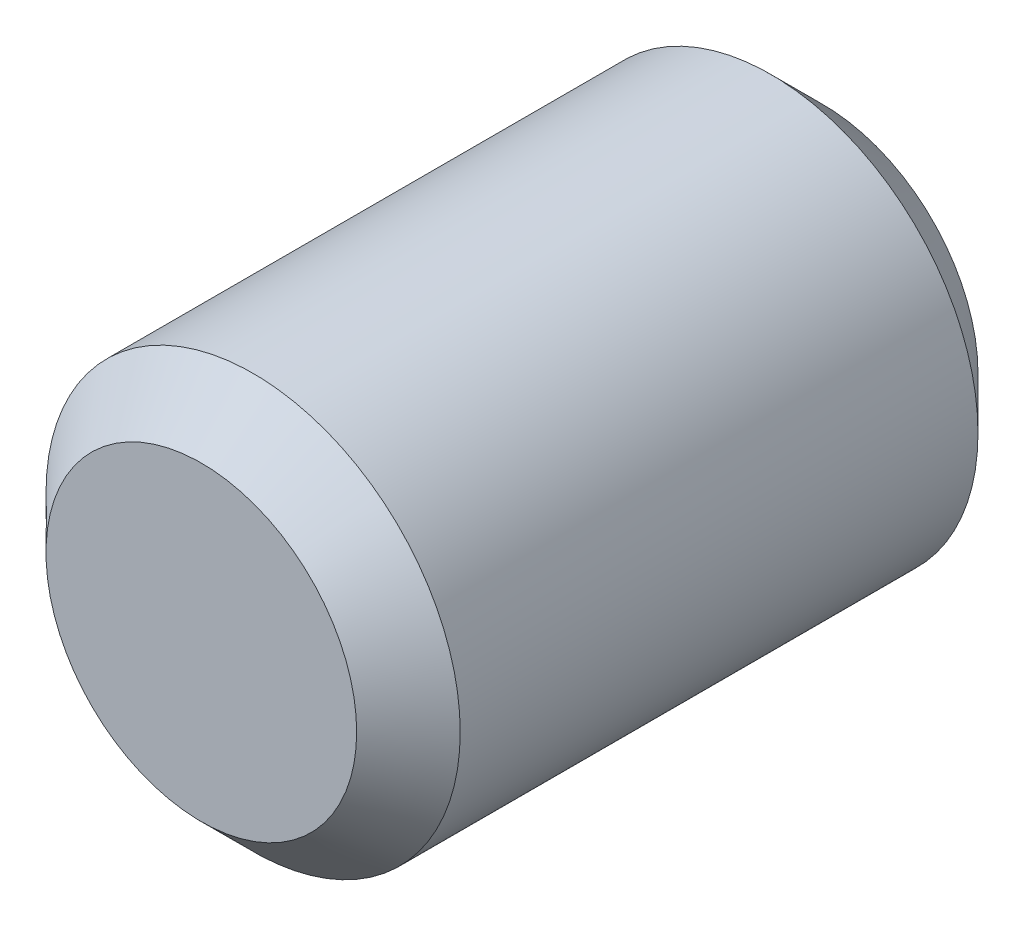
SolidWorks part; units mm, degrees
ref_plane "Front" through (0, 0, 0) normal (0, 0, 1) x (1, 0, 0)
ref_plane "Top" through (0, 0, 0) normal (0, 1, 0) x (1, 0, 0)
ref_plane "Right" through (0, 0, 0) normal (1, 0, 0) x (0, 0, -1)
sketch "Sketch1" plane through (0, 0, 0) normal (0, 0, 1) x (1, 0, 0)
  circle A0 centre (0, 0) radius 1
  dimension "D1" = 2
extrude "Boss-Extrude1" add sketch "Sketch1" along normal mid plane 3
chamfer "Chamfer1" distance 0.25 angle 45 2 edges at (1, 0, -1.5) (1, 0, 1.5)
